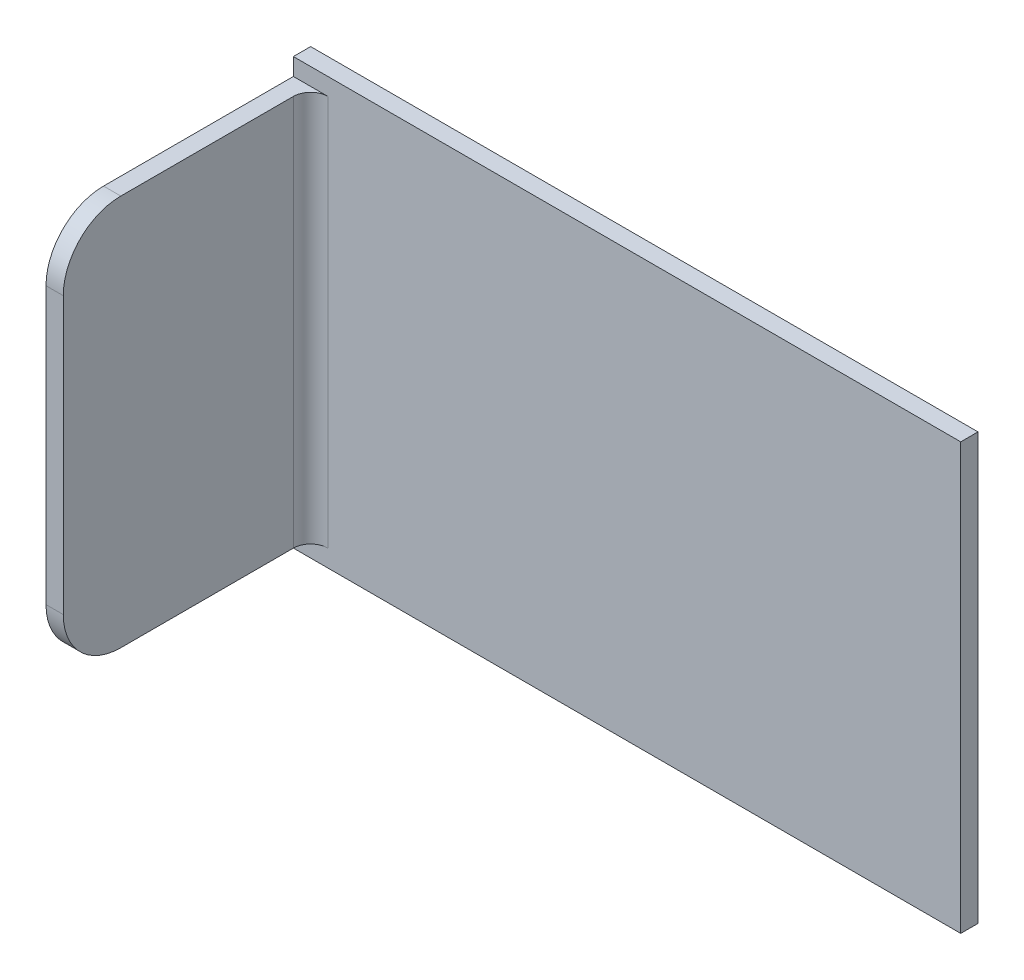
SolidWorks part; units mm, degrees
ref_plane "Plano frontal" through (0, 0, 0) normal (0, 0, 1) x (1, 0, 0)
ref_plane "Plano superior" through (0, 0, 0) normal (0, 1, 0) x (1, 0, 0)
ref_plane "Plano direito" through (0, 0, 0) normal (1, 0, 0) x (0, 0, -1)
sketch "Esboço1" plane through (0, 0, 0) normal (0, 0, 1) x (1, 0, 0)
  line L1 (-58, 37) -> (58, 37)
  line L2 (-58, 37) -> (-58, -37)
  line L3 (-58, -37) -> (58, -37)
  line L4 (58, 37) -> (58, -37)
  line L5 (-58, 37) -> (58, -37) construction
  line L6 (-58, -37) -> (58, 37) construction
  point P0 (0, 0)
  dimension "D1" = 74
  dimension "D2" = 116
extrude "Ressalto-extrusão1" add sketch "Esboço1" along normal blind 3
sketch "Esboço2" plane through (-58, 0, 0) normal (-1, 0, 0) x (0, 0, 1)
  line L5 (3, 34) -> (36, 34)
  line L6 (3, 37) -> (3, -37) construction
  line L7 (46, 24) -> (46, -24)
  line L8 (36, -34) -> (3, -34)
  line L9 (3, -34) -> (3, 34)
  line L10 (3, 37) -> (0, 37) construction
  line L11 (3, -37) -> (0, -37) construction
  arc A2 (46, -24) -> (36, -34) centre (36, -24) cw
  arc A3 (36, 34) -> (46, 24) centre (36, 24) cw
  dimension "D1" = 3
  dimension "D4" = 10
  dimension "D2" = 3
  dimension "D3" = 43
extrude "Ressalto-extrusão2" add sketch "Esboço2" against normal blind 3
fillet "Filete1" radius 3 1 edges at (-55, 0, 3)
